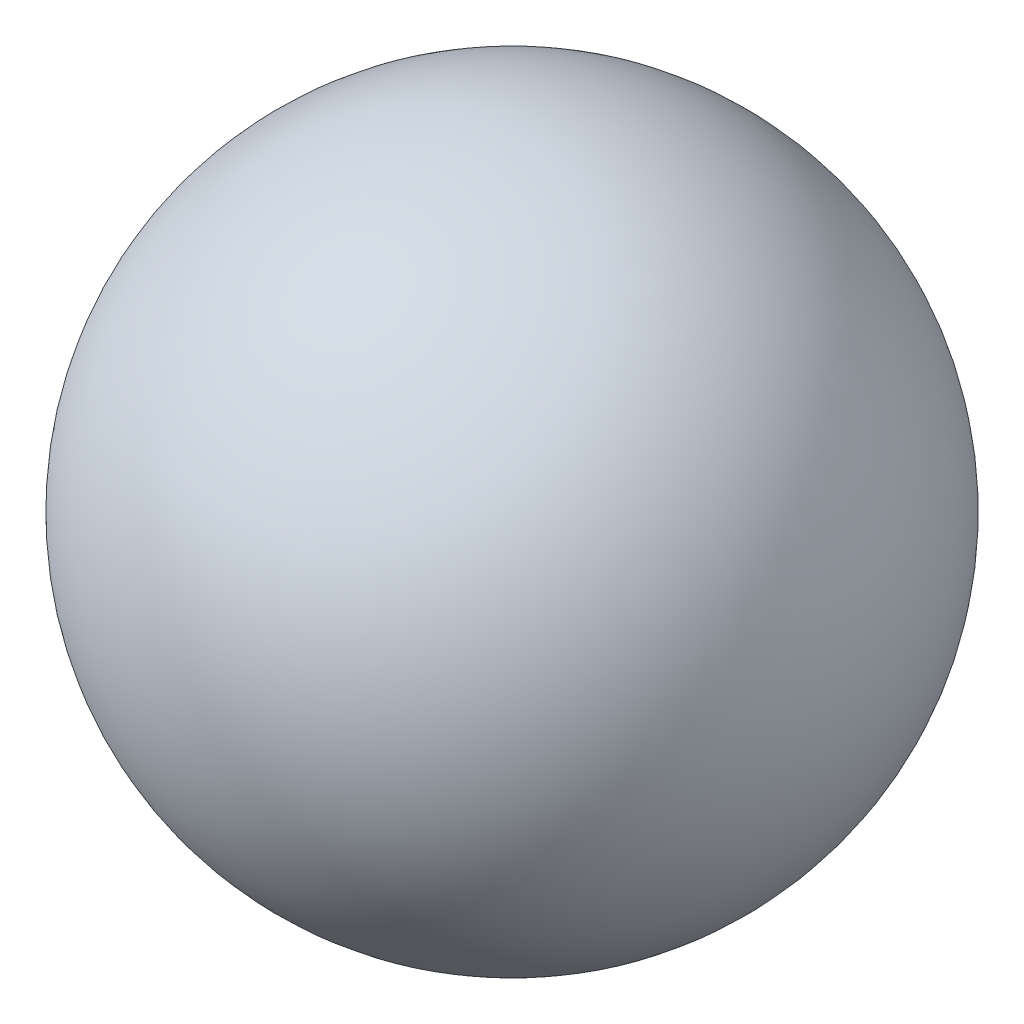
SolidWorks part; units mm, degrees
ref_plane "Płaszczyzna przednia" through (0, 0, 0) normal (0, 0, 1) x (1, 0, 0)
ref_plane "Płaszczyzna górna" through (0, 0, 0) normal (0, 1, 0) x (1, 0, 0)
ref_plane "Płaszczyzna prawa" through (0, 0, 0) normal (1, 0, 0) x (0, 0, -1)
sketch "Sketch1" plane through (0, 0, 0) normal (0, 0, 1) x (1, 0, 0)
  line L0 (0, 2.25) -> (0, -2.25)
  arc A0 (0, -2.25) -> (0, 2.25) centre (0, 0) ccw
  dimension "D1" = 4.5
revolve "Revolve1" add sketch "Sketch1" angle 360 about L0
